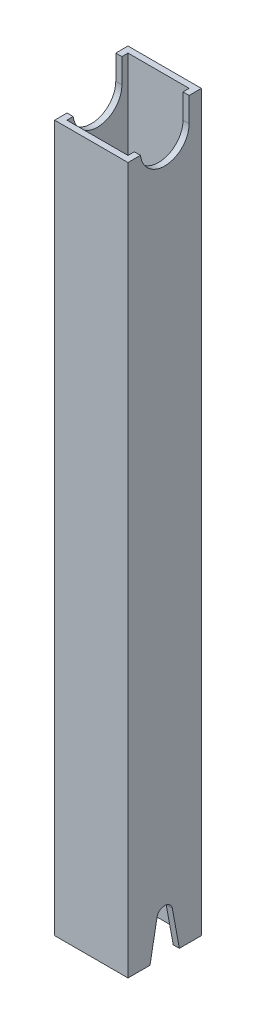
SolidWorks part; units mm, degrees
ref_plane "Front Plane" through (0, 0, 0) normal (0, 0, 1) x (1, 0, 0)
ref_plane "Top Plane" through (0, 0, 0) normal (0, 1, 0) x (1, 0, 0)
ref_plane "Right Plane" through (0, 0, 0) normal (1, 0, 0) x (0, 0, -1)
sketch "Sketch1" plane through (0, 0, 0) normal (0, 1, 0) x (1, 0, 0)
  line L1 (-12.5, 12.5) -> (12.5, 12.5)
  line L2 (-12.5, 12.5) -> (-12.5, -12.5)
  line L3 (-12.5, -12.5) -> (12.5, -12.5)
  line L4 (12.5, 12.5) -> (12.5, -12.5)
  line L5 (-12.5, 12.5) -> (12.5, -12.5) construction
  line L6 (-12.5, -12.5) -> (12.5, 12.5) construction
  line L7 (-15, 15) -> (15, 15)
  line L8 (-15, 15) -> (-15, -15)
  line L9 (-15, -15) -> (15, -15)
  line L10 (15, 15) -> (15, -15)
  line L11 (-15, 15) -> (15, -15) construction
  line L12 (-15, -15) -> (15, 15) construction
  point P0 (0, 0)
  point P6 (0, 0)
  dimension "D1" = 25
  dimension "D2" = 30
extrude "Boss-Extrude1" add sketch "Sketch1" along normal blind 300
hole_wizard "1/4 (0.25) Diameter Hole1" positions "Sketch3" profile "Sketch2" hole size "1/4" standard "ANSI Inch" end condition through all
sketch "Sketch3" plane through (-15, 0, 0) normal (-1, 0, 0) x (0, 0, 1)
  line L0 (-15, 0) -> (15, 0) construction
  point P0 (0, 15)
  dimension "D1" = 15
sketch "Sketch2" plane through (-15, 15, 0) normal (0, 1, 0) x (0, 0, 1)
  line L0 (0, 0) -> (0, 30)
  line L1 (0, 30) -> (3.175, 30)
  line L2 (3.175, 30) -> (3.175, 0)
  line L5 (3.175, 0) -> (0, 0)
  line L11 (0, -6.35) -> (0, 107.95) construction
  dimension "Thru Hole Dia." = 6.35
  dimension "Thru Hole Depth" = 30
sketch "Sketch4" plane through (-15, 0, 0) normal (-1, 0, 0) x (0, 0, 1)
  line L0 (-10, 300) -> (-10, 290)
  line L1 (-15, 300) -> (15, 300) construction
  line L2 (9.9216, 288.75) -> (15, 288.75)
  line L3 (15, 300) -> (15, 0) construction
  line L4 (15, 288.75) -> (15, 300)
  line L5 (15, 300) -> (-10, 300)
  arc A0 (-10, 290) -> (9.9216, 288.75) centre (0, 290) ccw
  dimension "D2" = 10
  dimension "D1" = 10
  dimension "D3" = 1.25
extrude "Cut-Extrude1" cut sketch "Sketch4" against normal through all
sketch "Sketch5" plane through (-15, 0, 0) normal (-1, 0, 0) x (0, 0, 1)
  line L0 (-3.1222, 15.5768) -> (-6, 0)
  line L1 (-15, 0) -> (15, 0) construction
  line L2 (-6, 0) -> (6, 0)
  line L3 (6, 0) -> (3.1222, 15.5768)
  circle A0 centre (0, 15) radius 3.175 construction
  arc A1 (3.1222, 15.5768) -> (-3.1222, 15.5768) centre (0, 15) ccw
  dimension "D1" = 12
extrude "Cut-Extrude2" cut sketch "Sketch5" against normal through all
